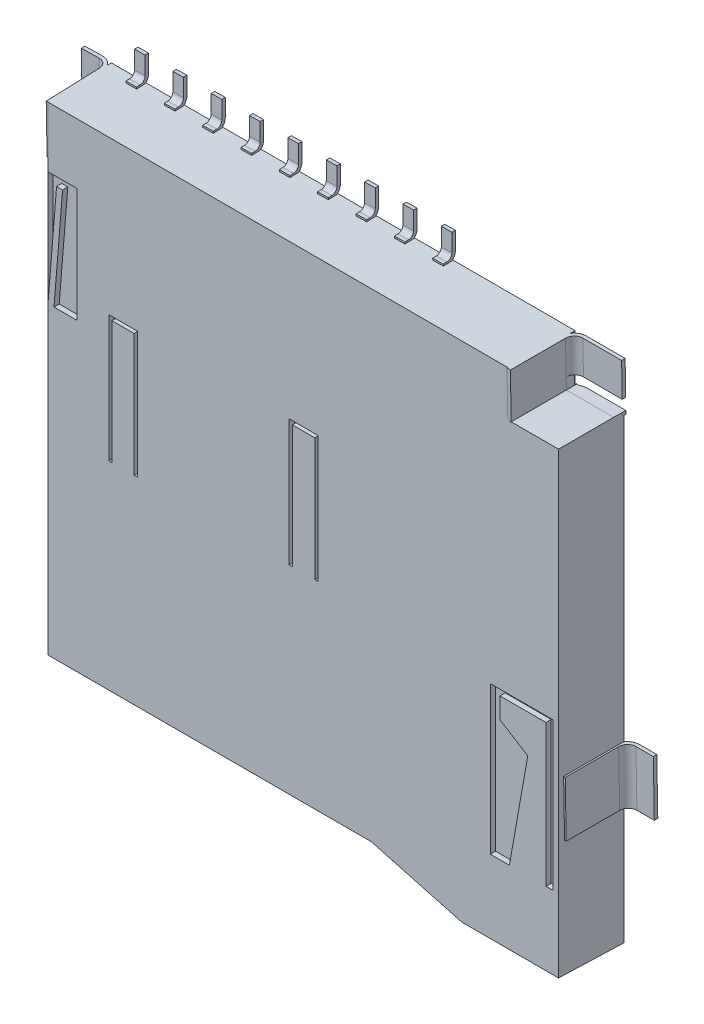
SolidWorks part; units mm, degrees
ref_plane "前视基准面" through (0, 0, 0) normal (0, 0, 1) x (1, 0, 0)
ref_plane "上视基准面" through (0, 0, 0) normal (0, 1, 0) x (1, 0, 0)
ref_plane "右视基准面" through (0, 0, 0) normal (1, 0, 0) x (0, 0, -1)
sketch "草图1" plane through (0, 0, 0) normal (0, 0, 1) x (1, 0, 0)
  line L0 (0, 0) -> (13.3, 0)
  line L1 (14.7071, -14.5) -> (14.7071, -1.3)
  line L2 (14.7071, -14.5) -> (11.9, -14.5)
  line L3 (9.3, -13.8) -> (11.9, -14.5)
  line L4 (9.3, -13.8) -> (0, -13.8)
  line L5 (0, -13.8) -> (0, 0)
  line L6 (13.3, 0) -> (13.3, -1.3)
  line L7 (13.3, -1.3) -> (14.7071, -1.3)
extrude "凸台-拉伸1" add sketch "草图1" along normal blind 1.85 draft 1
ref_plane "基准面5" through (0, -0.6999, -0.0122) normal (0, 0.9998, 0.0175) x (1, 0, 0)
sketch "草图17" plane through (0, -0.6999, -0.0122) normal (0, 0.9998, 0.0175) x (1, 0, 0)
  line L0 (13.2677, -1.873) -> (13.2949, -0.3175)
  line L1 (13.5948, -0.0227) -> (14.7071, -0.0227)
  arc A0 (13.5948, -0.0227) -> (13.2949, -0.3175) centre (13.5948, -0.3227) ccw
  point P8 (13.3, -0.0227)
  dimension "D1" = 0.3
extrude "拉伸-薄壁2" add sketch "草图17" along normal mid plane 1.4 thin thin type mid plane wall 0.1
sketch "草图27" plane through (0, -0.6999, -0.0122) normal (0, 0.9998, 0.0175) x (1, 0, 0)
  line L0 (0.0323, -1.8503) -> (0.0052, -0.3)
  line L1 (-0.3, -0.0052) -> (-0.8, -0.014)
  arc A0 (0.0052, -0.3) -> (-0.3, -0.0052) centre (-0.2947, -0.3052) ccw
  point P7 (0, 0)
  dimension "D1" = 0.3
extrude "拉伸-薄壁4" add sketch "草图27" along normal mid plane 1.4 thin thin type mid plane wall 0.1
ref_plane "基准面7" through (0, -10.2984, -0.1798) normal (0, 0.9998, 0.0175) x (1, 0, 0)
sketch "草图28" plane through (0, -10.2984, -0.1798) normal (0, 0.9998, 0.0175) x (1, 0, 0)
  line L0 (-0.0177, -1.8512) -> (-0.001, -0.3858)
  line L1 (-0.2617, -0.0849) -> (-0.8, -0.014)
  line L2 (-0.7992, -0.064) -> (-0.8009, 0.036) construction
  arc A0 (-0.2617, -0.0849) -> (-0.001, -0.3858) centre (-0.3009, -0.3824) cw
  point P9 (0.0021, -0.1197)
  dimension "D1" = 0.3
extrude "拉伸-薄壁5" add sketch "草图28" along normal mid plane 1.6 thin thin type mid plane wall 0.1
sketch "草图29" plane through (0, -10.2984, -0.1798) normal (0, 0.9998, 0.0175) x (1, 0, 0)
  line L0 (14.6748, -1.873) -> (14.7018, -0.3673)
  line L1 (15.0017, -0.0727) -> (15.5, -0.0727)
  arc A0 (15.0017, -0.0727) -> (14.7018, -0.3673) centre (15.0017, -0.3727) ccw
  point P7 (14.7071, -0.0727)
  dimension "D1" = 0.3
extrude "拉伸-薄壁6" add sketch "草图29" along normal mid plane 1.6 thin thin type mid plane wall 0.1
ref_plane "基准面8" through (0.8499, 0, -0.0148) normal (-0.9998, 0, 0.0175) x (0.0175, 0, 0.9998)
sketch "草图30" plane through (0.8499, 0, -0.0148) normal (-0.9998, 0, 0.0175) x (0.0175, 0, 0.9998)
  line L0 (0.3, -0.0053) -> (0.1965, -0.0034)
  line L1 (0, 0.1965) -> (0, 0.71)
  arc A0 (0, 0.1965) -> (0.1965, -0.0034) centre (0.2, 0.1965) ccw
  point P7 (0, 0)
  dimension "D1" = 0.2
extrude "拉伸-薄壁7" add sketch "草图30" along normal mid plane 0.3 thin thin type mid plane wall 0.1
pattern_linear "阵列(线性)1" count 9 spacing 1.1 along (1, 0, 0) of "拉伸-薄壁7"
sketch "草图33" plane through (0, -10.2984, -0.1798) normal (0, 0.9998, 0.0175) x (1, 0, 0)
  line L0 (0.469, -1.5958) -> (0.469, -0.44)
  line L1 (0.469, -0.44) -> (11.8879, -0.44)
  line L2 (11.8879, -0.44) -> (11.8879, -1.5958)
  line L3 (11.8879, -1.5958) -> (0.469, -1.5958)
  line L4 (0.469, -1.5958) -> (0.469, -1.5762)
extrude "切除-拉伸5" cut sketch "草图33" against normal mid plane 12 contours L0 L1 L2 L3
ref_plane "基准面10" through (0, 0, 2.7) normal (0, 0, 1) x (1, 0, 0)
sketch "草图38" plane through (0, 0, 2.7) normal (0, 0, 1) x (1, 0, 0)
  line L0 (13.3448, -0.9759) -> (14.7383, -0.9759)
  line L3 (13.3448, -0.0056) -> (13.3448, -1.3052) construction
  line L4 (14.7383, -0.9759) -> (14.7383, -1.3052)
  line L6 (14.7383, -1.3052) -> (13.3448, -1.3052)
  line L7 (13.3448, -1.3052) -> (13.3448, -0.9759)
extrude "切除-拉伸11" cut sketch "草图38" against normal through all
ref_plane "基准面11" through (0, 0, 0) normal (0, 0, 1) x (1, 0, 0)
sketch "草图39" plane through (0, 0, 0) normal (0, 0, 1) x (1, 0, 0)
  circle A0 centre (2.3, -10.5) radius 0.4
extrude "凸台-拉伸2" add sketch "草图39" against normal blind 0.6
sketch "草图40" plane through (0, 0, 0) normal (0, 0, 1) x (1, 0, 0)
  circle A0 centre (10.3, -10.5) radius 0.4
extrude "凸台-拉伸4" add sketch "草图40" against normal blind 0.6
sketch "草图41" plane through (0, 0, 2.7) normal (0, 0, 1) x (1, 0, 0)
  line L0 (0.0323, -1.763) -> (0.868, -1.763)
  line L1 (0.0323, -0.0323) -> (0.0323, -13.7677) construction
  line L2 (0.868, -1.763) -> (0.868, -5.038)
  line L3 (0.868, -5.038) -> (0.2042, -5.038)
  line L4 (0.2042, -5.038) -> (0.4502, -2.0064)
  line L5 (0.0323, -1.763) -> (0.0323, -5.038)
  line L6 (0.0323, -5.038) -> (0.2783, -2.0064)
  line L7 (0.2783, -2.0064) -> (0.4502, -2.0064)
extrude "切除-拉伸12" cut sketch "草图41" against normal blind 1
sketch "草图42" plane through (0, 0, 2.7) normal (0, 0, 1) x (1, 0, 0)
  line L0 (1.7753, -4.4405) -> (1.7753, -8.0695)
  line L1 (1.7753, -8.0695) -> (1.8663, -8.0695)
  line L2 (1.8663, -8.0695) -> (1.8663, -4.5454)
  line L3 (1.8663, -4.5454) -> (2.5014, -4.5454)
  line L4 (2.5014, -4.5454) -> (2.5014, -8.0695)
  line L5 (2.5014, -8.0695) -> (2.5923, -8.0695)
  line L6 (2.5923, -8.0695) -> (2.5923, -4.4405)
  line L7 (2.5923, -4.4405) -> (1.7753, -4.4405)
  line L8 (6.9457, -4.4405) -> (6.9457, -8.0695)
  line L9 (6.9457, -8.0695) -> (7.0405, -8.0695)
  line L10 (7.0405, -8.0695) -> (7.0405, -4.5454)
  line L11 (7.0405, -4.5454) -> (7.6861, -4.5454)
  line L12 (7.6861, -4.5454) -> (7.6861, -8.0695)
  line L13 (7.6861, -8.0695) -> (7.778, -8.0695)
  line L14 (7.778, -8.0695) -> (7.778, -4.4405)
  line L15 (7.778, -4.4405) -> (6.9457, -4.4405)
extrude "切除-拉伸13" cut sketch "草图42" against normal blind 1 contours L2 L3 L4 L5 L6 L7 L0 L1 | L14 L15 L8 L9 L10 L11 L12 L13
sketch "草图43" plane through (0, 0, 2.7) normal (0, 0, 1) x (1, 0, 0)
  line L0 (14.5202, -8.1329) -> (14.5202, -12.3707)
  line L1 (14.5202, -12.3707) -> (14.3157, -12.3707)
  line L2 (14.3157, -12.3707) -> (14.3157, -8.3002)
  line L3 (14.3157, -8.3002) -> (12.9961, -8.3002)
  line L4 (12.9961, -8.3002) -> (12.9961, -8.895)
  line L5 (12.9961, -8.895) -> (13.5351, -9.2295)
  line L6 (13.5351, -9.2295) -> (13.7928, -9.3895)
  line L7 (13.7928, -9.3895) -> (13.2656, -12.3707)
  line L8 (13.2656, -12.3707) -> (12.7173, -12.3707)
  line L9 (12.7173, -12.3707) -> (12.7173, -8.1329)
  line L10 (12.7173, -8.1329) -> (14.5202, -8.1329)
extrude "切除-拉伸14" cut sketch "草图43" against normal blind 1
